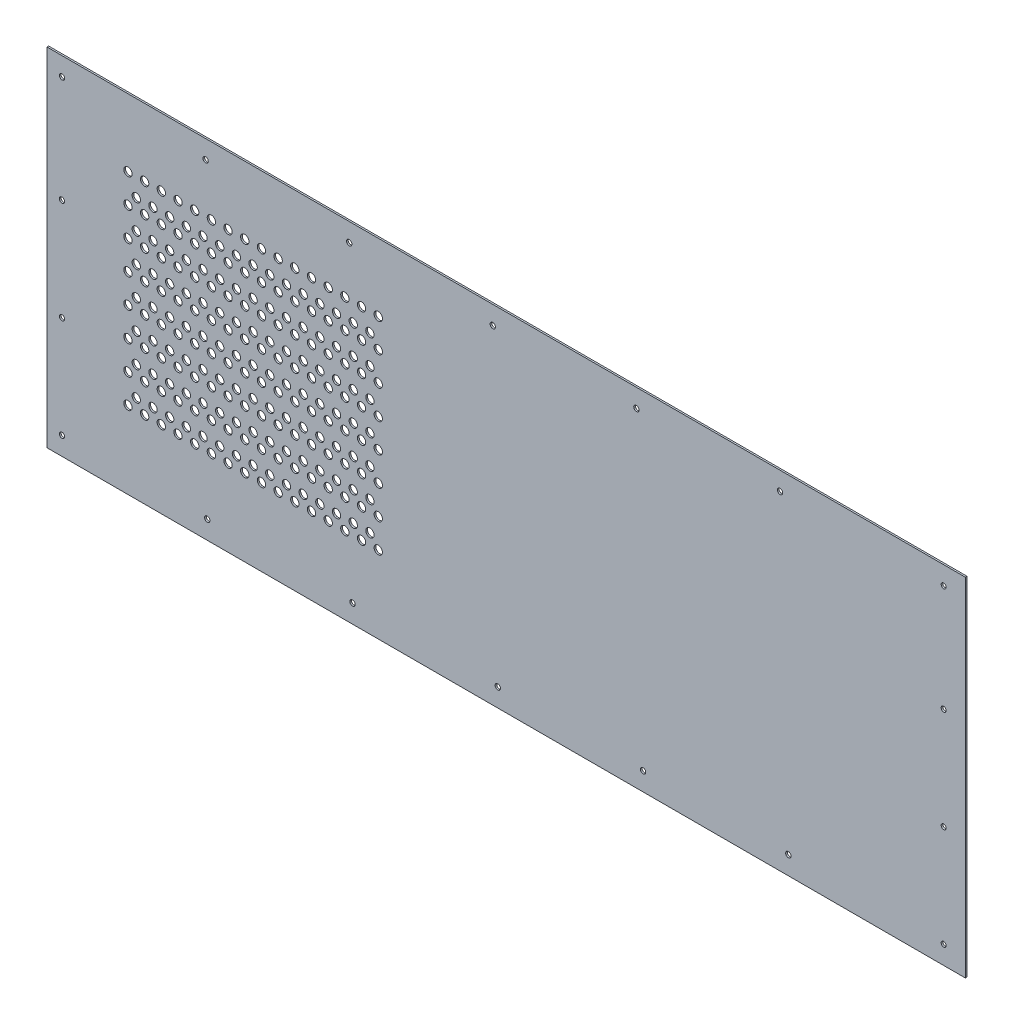
SolidWorks part; units mm, degrees
material "Nikiel"
ref_plane "Płaszczyzna przednia" through (0, 0, 0) normal (0, 0, 1) x (1, 0, 0)
ref_plane "Płaszczyzna górna" through (0, 0, 0) normal (0, 1, 0) x (1, 0, 0)
ref_plane "Płaszczyzna prawa" through (0, 0, 0) normal (1, 0, 0) x (0, 0, -1)
sketch "Szkic1" plane through (0, 0, 0) normal (0, 0, 1) x (1, 0, 0)
  line L1 (-39.6516, 30.4786) -> (67.6913, 30.4786)
  line L2 (-39.6516, 30.4786) -> (-39.6516, -40.6786)
  line L3 (-39.6516, -40.6786) -> (67.6913, -40.6786)
  line L4 (67.6913, 30.4786) -> (67.6913, -40.6786)
extrude "Dodanie-wyciągnięcie1" add sketch "Szkic1" along normal blind 1
sketch "Szkic2" plane through (-39.6516, 0, 0) normal (-1, 0, 0) x (0, 0, 1)
  line L1 (0, -40.6786) -> (1, -40.6786)
  line L2 (0, -40.6786) -> (0, 30.4786)
  line L3 (0, 30.4786) -> (1, 30.4786)
  line L4 (1, -40.6786) -> (1, 30.4786)
extrude "Dodanie-wyciągnięcie2" add sketch "Szkic2" along normal up to surface (442.9725 mm away)
sketch "Szkic3" plane through (0, 30.4786, 0) normal (0, 1, 0) x (1, 0, 0)
  line L1 (67.6913, 0) -> (-482.6241, 0)
  line L2 (67.6913, 0) -> (67.6913, -1)
  line L3 (67.6913, -1) -> (-482.6241, -1)
  line L4 (-482.6241, 0) -> (-482.6241, -1)
extrude "Dodanie-wyciągnięcie3" add sketch "Szkic3" along normal up to surface (137.8429 mm away)
sketch "Szkic4" plane through (0, 168.3214, 0) normal (0, 1, 0) x (1, 0, 0)
  line L1 (67.6913, 0) -> (-482.6241, 0)
  line L2 (67.6913, 0) -> (67.6913, -1)
  line L3 (67.6913, -1) -> (-482.6241, -1)
  line L4 (-482.6241, 0) -> (-482.6241, -1)
extrude "Dodanie-wyciągnięcie4" add sketch "Szkic4" along normal blind 3
sketch "Szkic5" plane through (0, 0, 0) normal (0, 0, -1) x (-1, 0, 0)
  line L0 (432.6241, -0.6786) -> (432.6241, 131.3214) construction
  line L1 (436.6094, 131.3214) -> (286.6418, 131.3214) construction
  line L2 (286.6418, 131.3214) -> (286.6418, -35.1631) construction
  line L3 (286.6241, -0.6786) -> (432.6241, -0.6786) construction
  line L4 (482.6241, 171.3214) -> (-67.6913, 171.3214) construction
  line L5 (482.6241, 171.3214) -> (482.6241, -40.6786) construction
  line L6 (482.6241, -40.6786) -> (-67.6913, -40.6786) construction
  line L7 (436.6094, 114.0014) -> (286.6418, 114.0014) construction
  line L8 (436.6094, 96.6814) -> (286.6418, 96.6814) construction
  line L9 (436.6094, 79.3614) -> (286.6418, 79.3614) construction
  line L10 (436.6094, 62.0414) -> (286.6418, 62.0414) construction
  line L11 (436.6094, 44.7214) -> (286.6418, 44.7214) construction
  line L12 (436.6094, 27.4014) -> (286.6418, 27.4014) construction
  line L13 (436.6094, 10.0814) -> (286.6418, 10.0814) construction
  line L14 (486.7449, 171.8499) -> (486.7449, -40.0624) construction
  line L15 (486.7449, 65.8938) -> (219.178, 65.8938) construction
  circle A3 centre (434.1094, 128.8214) radius 2.5
  circle A4 centre (424.1094, 128.8214) radius 2.5
  circle A5 centre (414.1094, 128.8214) radius 2.5
  circle A6 centre (404.1094, 128.8214) radius 2.5
  circle A7 centre (394.1094, 128.8214) radius 2.5
  circle A8 centre (384.1094, 128.8214) radius 2.5
  circle A9 centre (374.1094, 128.8214) radius 2.5
  circle A10 centre (364.1094, 128.8214) radius 2.5
  circle A11 centre (354.1094, 128.8214) radius 2.5
  circle A12 centre (344.1094, 128.8214) radius 2.5
  circle A13 centre (334.1094, 128.8214) radius 2.5
  circle A14 centre (324.1094, 128.8214) radius 2.5
  circle A15 centre (314.1094, 128.8214) radius 2.5
  circle A16 centre (304.1094, 128.8214) radius 2.5
  circle A17 centre (294.1094, 128.8214) radius 2.5
  circle A18 centre (284.1094, 128.8214) radius 2.5
  circle A21 centre (429.1094, 117.8538) radius 2.5
  circle A22 centre (419.1094, 117.8538) radius 2.5
  circle A23 centre (409.1094, 117.8538) radius 2.5
  circle A24 centre (399.1094, 117.8538) radius 2.5
  circle A25 centre (389.1094, 117.8538) radius 2.5
  circle A26 centre (379.1094, 117.8538) radius 2.5
  circle A27 centre (369.1094, 117.8538) radius 2.5
  circle A28 centre (359.1094, 117.8538) radius 2.5
  circle A29 centre (349.1094, 117.8538) radius 2.5
  circle A30 centre (339.1094, 117.8538) radius 2.5
  circle A31 centre (329.1094, 117.8538) radius 2.5
  circle A32 centre (319.1094, 117.8538) radius 2.5
  circle A33 centre (309.1094, 117.8538) radius 2.5
  circle A34 centre (299.1094, 117.8538) radius 2.5
  circle A35 centre (289.1094, 117.8538) radius 2.5
  circle A36 centre (434.1094, 111.5014) radius 2.5
  circle A37 centre (424.1094, 111.5014) radius 2.5
  circle A38 centre (414.1094, 111.5014) radius 2.5
  circle A39 centre (404.1094, 111.5014) radius 2.5
  circle A40 centre (394.1094, 111.5014) radius 2.5
  circle A41 centre (384.1094, 111.5014) radius 2.5
  circle A42 centre (374.1094, 111.5014) radius 2.5
  circle A43 centre (364.1094, 111.5014) radius 2.5
  circle A44 centre (354.1094, 111.5014) radius 2.5
  circle A45 centre (344.1094, 111.5014) radius 2.5
  circle A46 centre (334.1094, 111.5014) radius 2.5
  circle A47 centre (324.1094, 111.5014) radius 2.5
  circle A48 centre (314.1094, 111.5014) radius 2.5
  circle A49 centre (304.1094, 111.5014) radius 2.5
  circle A50 centre (294.1094, 111.5014) radius 2.5
  circle A51 centre (284.1094, 111.5014) radius 2.5
  circle A52 centre (429.1094, 100.5338) radius 2.5
  circle A53 centre (419.1094, 100.5338) radius 2.5
  circle A54 centre (409.1094, 100.5338) radius 2.5
  circle A55 centre (399.1094, 100.5338) radius 2.5
  circle A56 centre (389.1094, 100.5338) radius 2.5
  circle A57 centre (379.1094, 100.5338) radius 2.5
  circle A58 centre (369.1094, 100.5338) radius 2.5
  circle A59 centre (359.1094, 100.5338) radius 2.5
  circle A60 centre (349.1094, 100.5338) radius 2.5
  circle A61 centre (339.1094, 100.5338) radius 2.5
  circle A62 centre (329.1094, 100.5338) radius 2.5
  circle A63 centre (319.1094, 100.5338) radius 2.5
  circle A64 centre (309.1094, 100.5338) radius 2.5
  circle A65 centre (299.1094, 100.5338) radius 2.5
  circle A66 centre (289.1094, 100.5338) radius 2.5
  circle A67 centre (434.1094, 94.1814) radius 2.5
  circle A68 centre (424.1094, 94.1814) radius 2.5
  circle A69 centre (414.1094, 94.1814) radius 2.5
  circle A70 centre (404.1094, 94.1814) radius 2.5
  circle A71 centre (394.1094, 94.1814) radius 2.5
  circle A72 centre (384.1094, 94.1814) radius 2.5
  circle A73 centre (374.1094, 94.1814) radius 2.5
  circle A74 centre (364.1094, 94.1814) radius 2.5
  circle A75 centre (354.1094, 94.1814) radius 2.5
  circle A76 centre (344.1094, 94.1814) radius 2.5
  circle A77 centre (334.1094, 94.1814) radius 2.5
  circle A78 centre (324.1094, 94.1814) radius 2.5
  circle A79 centre (314.1094, 94.1814) radius 2.5
  circle A80 centre (304.1094, 94.1814) radius 2.5
  circle A81 centre (294.1094, 94.1814) radius 2.5
  circle A82 centre (284.1094, 94.1814) radius 2.5
  circle A83 centre (429.1094, 83.2138) radius 2.5
  circle A84 centre (419.1094, 83.2138) radius 2.5
  circle A85 centre (409.1094, 83.2138) radius 2.5
  circle A86 centre (399.1094, 83.2138) radius 2.5
  circle A87 centre (389.1094, 83.2138) radius 2.5
  circle A88 centre (379.1094, 83.2138) radius 2.5
  circle A89 centre (369.1094, 83.2138) radius 2.5
  circle A90 centre (359.1094, 83.2138) radius 2.5
  circle A91 centre (349.1094, 83.2138) radius 2.5
  circle A92 centre (339.1094, 83.2138) radius 2.5
  circle A93 centre (329.1094, 83.2138) radius 2.5
  circle A94 centre (319.1094, 83.2138) radius 2.5
  circle A95 centre (309.1094, 83.2138) radius 2.5
  circle A96 centre (299.1094, 83.2138) radius 2.5
  circle A97 centre (289.1094, 83.2138) radius 2.5
  circle A98 centre (434.1094, 76.8614) radius 2.5
  circle A99 centre (424.1094, 76.8614) radius 2.5
  circle A100 centre (414.1094, 76.8614) radius 2.5
  circle A101 centre (404.1094, 76.8614) radius 2.5
  circle A102 centre (394.1094, 76.8614) radius 2.5
  circle A103 centre (384.1094, 76.8614) radius 2.5
  circle A104 centre (374.1094, 76.8614) radius 2.5
  circle A105 centre (364.1094, 76.8614) radius 2.5
  circle A106 centre (354.1094, 76.8614) radius 2.5
  circle A107 centre (344.1094, 76.8614) radius 2.5
  circle A108 centre (334.1094, 76.8614) radius 2.5
  circle A109 centre (324.1094, 76.8614) radius 2.5
  circle A110 centre (314.1094, 76.8614) radius 2.5
  circle A111 centre (304.1094, 76.8614) radius 2.5
  circle A112 centre (294.1094, 76.8614) radius 2.5
  circle A113 centre (284.1094, 76.8614) radius 2.5
  circle A114 centre (429.1094, 65.8938) radius 2.5
  circle A115 centre (419.1094, 65.8938) radius 2.5
  circle A116 centre (409.1094, 65.8938) radius 2.5
  circle A117 centre (399.1094, 65.8938) radius 2.5
  circle A118 centre (389.1094, 65.8938) radius 2.5
  circle A119 centre (379.1094, 65.8938) radius 2.5
  circle A120 centre (369.1094, 65.8938) radius 2.5
  circle A121 centre (359.1094, 65.8938) radius 2.5
  circle A122 centre (349.1094, 65.8938) radius 2.5
  circle A123 centre (339.1094, 65.8938) radius 2.5
  circle A124 centre (329.1094, 65.8938) radius 2.5
  circle A125 centre (319.1094, 65.8938) radius 2.5
  circle A126 centre (309.1094, 65.8938) radius 2.5
  circle A127 centre (299.1094, 65.8938) radius 2.5
  circle A128 centre (289.1094, 65.8938) radius 2.5
  circle A129 centre (434.1094, 59.5414) radius 2.5
  circle A130 centre (424.1094, 59.5414) radius 2.5
  circle A131 centre (414.1094, 59.5414) radius 2.5
  circle A132 centre (404.1094, 59.5414) radius 2.5
  circle A133 centre (394.1094, 59.5414) radius 2.5
  circle A134 centre (384.1094, 59.5414) radius 2.5
  circle A135 centre (374.1094, 59.5414) radius 2.5
  circle A136 centre (364.1094, 59.5414) radius 2.5
  circle A137 centre (354.1094, 59.5414) radius 2.5
  circle A138 centre (344.1094, 59.5414) radius 2.5
  circle A139 centre (334.1094, 59.5414) radius 2.5
  circle A140 centre (324.1094, 59.5414) radius 2.5
  circle A141 centre (314.1094, 59.5414) radius 2.5
  circle A142 centre (304.1094, 59.5414) radius 2.5
  circle A143 centre (294.1094, 59.5414) radius 2.5
  circle A144 centre (284.1094, 59.5414) radius 2.5
  circle A145 centre (429.1094, 48.5738) radius 2.5
  circle A146 centre (419.1094, 48.5738) radius 2.5
  circle A147 centre (409.1094, 48.5738) radius 2.5
  circle A148 centre (399.1094, 48.5738) radius 2.5
  circle A149 centre (389.1094, 48.5738) radius 2.5
  circle A150 centre (379.1094, 48.5738) radius 2.5
  circle A151 centre (369.1094, 48.5738) radius 2.5
  circle A152 centre (359.1094, 48.5738) radius 2.5
  circle A153 centre (349.1094, 48.5738) radius 2.5
  circle A154 centre (339.1094, 48.5738) radius 2.5
  circle A155 centre (329.1094, 48.5738) radius 2.5
  circle A156 centre (319.1094, 48.5738) radius 2.5
  circle A157 centre (309.1094, 48.5738) radius 2.5
  circle A158 centre (299.1094, 48.5738) radius 2.5
  circle A159 centre (289.1094, 48.5738) radius 2.5
  circle A160 centre (434.1094, 42.2214) radius 2.5
  circle A161 centre (424.1094, 42.2214) radius 2.5
  circle A162 centre (414.1094, 42.2214) radius 2.5
  circle A163 centre (404.1094, 42.2214) radius 2.5
  circle A164 centre (394.1094, 42.2214) radius 2.5
  circle A165 centre (384.1094, 42.2214) radius 2.5
  circle A166 centre (374.1094, 42.2214) radius 2.5
  circle A167 centre (364.1094, 42.2214) radius 2.5
  circle A168 centre (354.1094, 42.2214) radius 2.5
  circle A169 centre (344.1094, 42.2214) radius 2.5
  circle A170 centre (334.1094, 42.2214) radius 2.5
  circle A171 centre (324.1094, 42.2214) radius 2.5
  circle A172 centre (314.1094, 42.2214) radius 2.5
  circle A173 centre (304.1094, 42.2214) radius 2.5
  circle A174 centre (294.1094, 42.2214) radius 2.5
  circle A175 centre (284.1094, 42.2214) radius 2.5
  circle A176 centre (429.1094, 31.2538) radius 2.5
  circle A177 centre (419.1094, 31.2538) radius 2.5
  circle A178 centre (409.1094, 31.2538) radius 2.5
  circle A179 centre (399.1094, 31.2538) radius 2.5
  circle A180 centre (389.1094, 31.2538) radius 2.5
  circle A181 centre (379.1094, 31.2538) radius 2.5
  circle A182 centre (369.1094, 31.2538) radius 2.5
  circle A183 centre (359.1094, 31.2538) radius 2.5
  circle A184 centre (349.1094, 31.2538) radius 2.5
  circle A185 centre (339.1094, 31.2538) radius 2.5
  circle A186 centre (329.1094, 31.2538) radius 2.5
  circle A187 centre (319.1094, 31.2538) radius 2.5
  circle A188 centre (309.1094, 31.2538) radius 2.5
  circle A189 centre (299.1094, 31.2538) radius 2.5
  circle A190 centre (289.1094, 31.2538) radius 2.5
  circle A191 centre (434.1094, 24.9014) radius 2.5
  circle A192 centre (424.1094, 24.9014) radius 2.5
  circle A193 centre (414.1094, 24.9014) radius 2.5
  circle A194 centre (404.1094, 24.9014) radius 2.5
  circle A195 centre (394.1094, 24.9014) radius 2.5
  circle A196 centre (384.1094, 24.9014) radius 2.5
  circle A197 centre (374.1094, 24.9014) radius 2.5
  circle A198 centre (364.1094, 24.9014) radius 2.5
  circle A199 centre (354.1094, 24.9014) radius 2.5
  circle A200 centre (344.1094, 24.9014) radius 2.5
  circle A201 centre (334.1094, 24.9014) radius 2.5
  circle A202 centre (324.1094, 24.9014) radius 2.5
  circle A203 centre (314.1094, 24.9014) radius 2.5
  circle A204 centre (304.1094, 24.9014) radius 2.5
  circle A205 centre (294.1094, 24.9014) radius 2.5
  circle A206 centre (284.1094, 24.9014) radius 2.5
  circle A207 centre (429.1094, 13.9338) radius 2.5
  circle A208 centre (419.1094, 13.9338) radius 2.5
  circle A209 centre (409.1094, 13.9338) radius 2.5
  circle A210 centre (399.1094, 13.9338) radius 2.5
  circle A211 centre (389.1094, 13.9338) radius 2.5
  circle A212 centre (379.1094, 13.9338) radius 2.5
  circle A213 centre (369.1094, 13.9338) radius 2.5
  circle A214 centre (359.1094, 13.9338) radius 2.5
  circle A215 centre (349.1094, 13.9338) radius 2.5
  circle A216 centre (339.1094, 13.9338) radius 2.5
  circle A217 centre (329.1094, 13.9338) radius 2.5
  circle A218 centre (319.1094, 13.9338) radius 2.5
  circle A219 centre (309.1094, 13.9338) radius 2.5
  circle A220 centre (299.1094, 13.9338) radius 2.5
  circle A221 centre (289.1094, 13.9338) radius 2.5
  circle A222 centre (434.1094, 7.5814) radius 2.5
  circle A223 centre (424.1094, 7.5814) radius 2.5
  circle A224 centre (414.1094, 7.5814) radius 2.5
  circle A225 centre (404.1094, 7.5814) radius 2.5
  circle A226 centre (394.1094, 7.5814) radius 2.5
  circle A227 centre (384.1094, 7.5814) radius 2.5
  circle A228 centre (374.1094, 7.5814) radius 2.5
  circle A229 centre (364.1094, 7.5814) radius 2.5
  circle A230 centre (354.1094, 7.5814) radius 2.5
  circle A231 centre (344.1094, 7.5814) radius 2.5
  circle A232 centre (334.1094, 7.5814) radius 2.5
  circle A233 centre (324.1094, 7.5814) radius 2.5
  circle A234 centre (314.1094, 7.5814) radius 2.5
  circle A235 centre (304.1094, 7.5814) radius 2.5
  circle A236 centre (294.1094, 7.5814) radius 2.5
  circle A237 centre (284.1094, 7.5814) radius 2.5
  circle A253 centre (289.1094, -3.3862) radius 2.5 [skipped]
  circle A254 centre (299.1094, -3.3862) radius 2.5 [skipped]
  circle A255 centre (309.1094, -3.3862) radius 2.5 [skipped]
  circle A256 centre (319.1094, -3.3862) radius 2.5 [skipped]
  circle A257 centre (329.1094, -3.3862) radius 2.5 [skipped]
  circle A258 centre (339.1094, -3.3862) radius 2.5 [skipped]
  circle A259 centre (349.1094, -3.3862) radius 2.5 [skipped]
  circle A260 centre (379.1094, -3.3862) radius 2.5 [skipped]
  circle A261 centre (369.1094, -3.3862) radius 2.5 [skipped]
  circle A262 centre (359.1094, -3.3862) radius 2.5 [skipped]
  circle A263 centre (409.1094, -3.3862) radius 2.5 [skipped]
  circle A264 centre (399.1094, -3.3862) radius 2.5 [skipped]
  circle A265 centre (389.1094, -3.3862) radius 2.5 [skipped]
  circle A266 centre (419.1094, -3.3862) radius 2.5 [skipped]
  circle A267 centre (429.1094, -3.3862) radius 2.5 [skipped]
  dimension "D5" = 16
  dimension "D6" = 15
  dimension "D1" = 40
  dimension "D2" = 50
  dimension "D3" = 40
  dimension "D4" = 150
  dimension "D7" = 8
extrude "Wytnij-wyciągnięcie1" cut sketch "Szkic5" against normal through all
sketch "Szkic6" plane through (0, 0, 1) normal (0, 0, 1) x (1, 0, 0)
  line L0 (42.6759, 158.3214) -> (48.6959, 158.3214) construction
  line L1 (48.6959, 158.3214) -> (48.6959, -121.1942) construction
  line L2 (-38.3741, -27.6786) -> (88.6157, -27.6786) construction
  line L3 (67.6913, -40.6786) -> (67.6913, 171.3214) construction
  line L4 (54.6913, -39.207) -> (54.6913, 277.7761) construction
  circle A1 centre (-473.6241, 158.3214) radius 1.6
  circle A8 centre (-387.5741, 158.3214) radius 1.6
  circle A9 centre (-301.5241, 158.3214) radius 1.6
  circle A10 centre (-215.4741, 158.3214) radius 1.6
  circle A11 centre (-129.4241, 158.3214) radius 1.6
  circle A12 centre (-43.3741, 158.3214) radius 1.6
  circle A14 centre (-473.6241, -27.6786) radius 1.6
  circle A15 centre (-386.5741, -27.6786) radius 1.6
  circle A16 centre (-299.5241, -27.6786) radius 1.6
  circle A17 centre (-212.4741, -27.6786) radius 1.6
  circle A18 centre (-125.4241, -27.6786) radius 1.6
  circle A19 centre (-38.3741, -27.6786) radius 1.6
  circle A21 centre (-473.6241, 33.3214) radius 1.6
  circle A22 centre (-473.6241, 94.3214) radius 1.6
  circle A25 centre (54.6913, 94.3214) radius 1.5
  circle A26 centre (54.6913, -27.6786) radius 1.5
  circle A27 centre (54.6913, 158.3214) radius 1.5
  circle A28 centre (42.6759, 158.3214) radius 1.6 [skipped]
  circle A29 centre (54.6913, 33.3214) radius 1.5
  circle A30 centre (48.6759, -27.6786) radius 1.6 [skipped]
  dimension "D1" = 18.9954
  dimension "D3" = 7
  dimension "D2" = 7
  dimension "D4" = 13
  dimension "D5" = 3
extrude "Wytnij-wyciągnięcie2" cut sketch "Szkic6" against normal through all
sketch "Szkic7" plane through (0, 0, 1) normal (0, 0, 1) x (1, 0, 0)
  line L0 (67.6913, -40.6786) -> (67.6913, 171.3214) construction
  line L1 (67.6913, -38.6786) -> (-482.6241, -38.6786)
  line L2 (67.6913, -38.6786) -> (67.6913, -40.6786)
  line L3 (67.6913, -40.6786) -> (-482.6241, -40.6786)
  line L4 (-482.6241, -38.6786) -> (-482.6241, -40.6786)
  line L5 (-482.6241, -38.6786) -> (67.6913, -38.6786) construction
extrude "Wytnij-wyciągnięcie3" cut sketch "Szkic7" against normal through all
sketch "Szkic8" plane through (0, 0, 1) normal (0, 0, 1) x (1, 0, 0)
  line L0 (-482.6241, 171.3214) -> (-482.6241, -38.6786) construction
  line L1 (67.6913, 171.3214) -> (-482.6241, 171.3214)
  line L2 (67.6913, 171.3214) -> (67.6913, 169.3214)
  line L3 (67.6913, 169.3214) -> (-482.6241, 169.3214)
  line L4 (-482.6241, 171.3214) -> (-482.6241, 169.3214)
  dimension "D1" = 2
extrude "Wytnij-wyciągnięcie4" cut sketch "Szkic8" against normal through all
